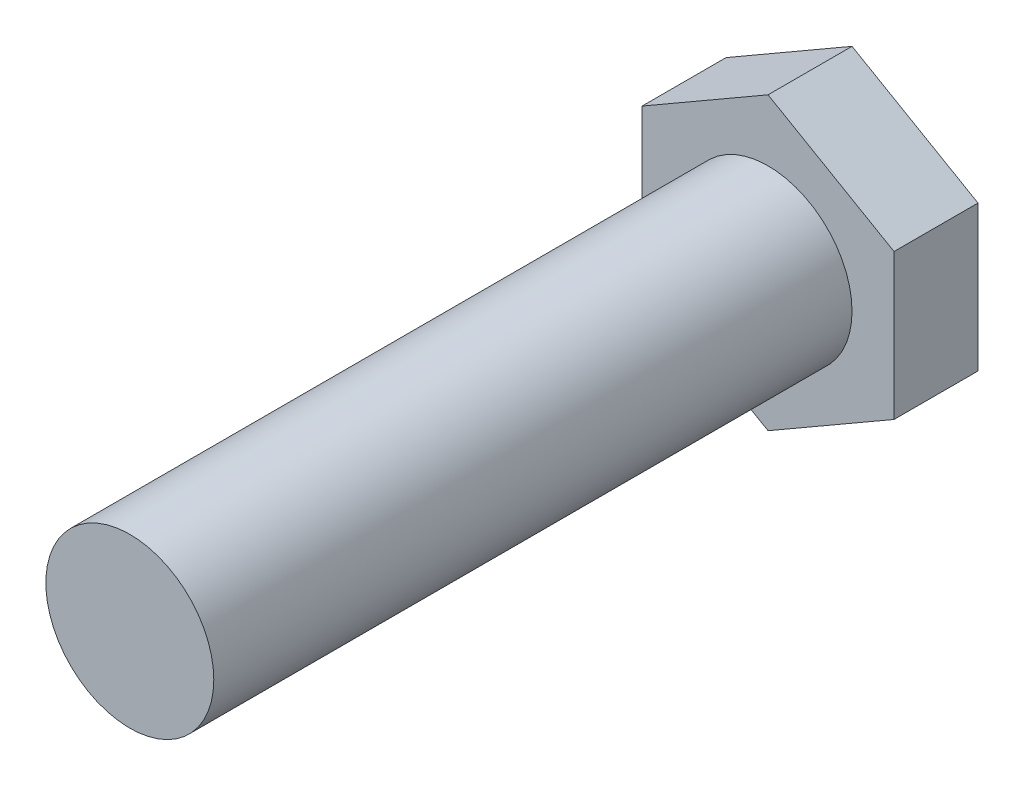
SolidWorks part; units mm, degrees
material "Alloy Steel (SS)"
ref_plane "Front Plane" through (0, 0, 0) normal (0, 0, 1) x (1, 0, 0)
ref_plane "Top Plane" through (0, 0, 0) normal (0, 1, 0) x (1, 0, 0)
ref_plane "Right Plane" through (0, 0, 0) normal (1, 0, 0) x (0, 0, -1)
sketch "Sketch1" plane through (0, 0, 0) normal (0, 0, 1) x (1, 0, 0)
  line L0 (0, 0) -> (0, 8.6603) construction
  line L2 (0, 8.6603) -> (-7.5, 4.3301)
  line L3 (-7.5, 4.3301) -> (-7.5, -4.3301)
  line L4 (-7.5, -4.3301) -> (0, -8.6603)
  line L5 (0, -8.6603) -> (7.5, -4.3301)
  line L6 (7.5, -4.3301) -> (7.5, 4.3301)
  line L7 (7.5, 4.3301) -> (0, 8.6603)
  circle A0 centre (0, 0) radius 7.5 construction
  circle A1 centre (0, 0) radius 5 construction
  dimension "D1" = 10
  dimension "D2" = 2.5
extrude "Boss-Extrude1" add sketch "Sketch1" along normal blind 5
sketch "Sketch2" plane through (0, 0, 5) normal (0, 0, 1) x (1, 0, 0)
  circle A0 centre (0, 0) radius 5
  circle A1 centre (0, 0) radius 5 construction
extrude "Boss-Extrude2" add sketch "Sketch2" along normal blind 38
cosmetic thread "Cosmetic Thread1" parameters "D1"=11, "D2"=8.344
